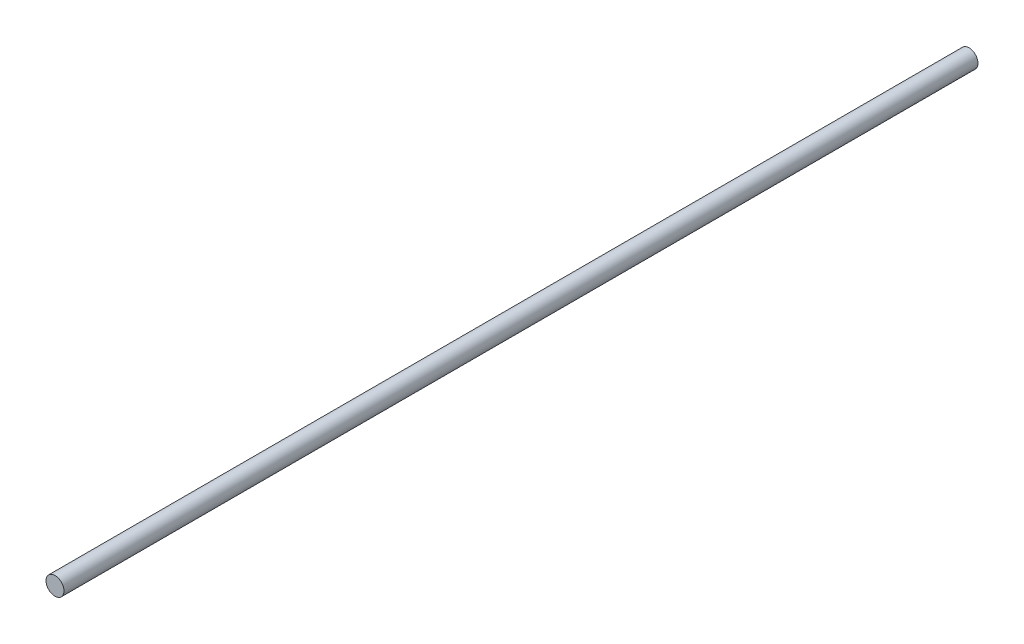
SolidWorks part; units mm, degrees
ref_plane "Front Plane" through (0, 0, 0) normal (0, 0, 1) x (1, 0, 0)
ref_plane "Top Plane" through (0, 0, 0) normal (0, 1, 0) x (1, 0, 0)
ref_plane "Right Plane" through (0, 0, 0) normal (1, 0, 0) x (0, 0, -1)
sketch "Sketch1" plane through (0, 0, 5) normal (0, 0, 1) x (1, 0, 0)
  circle A0 centre (1299.8728, 107.1307) radius 6 construction
  circle A1 centre (1299.8728, 107.1307) radius 6
extrude "Boss-Extrude1" add sketch "Sketch1" against normal up to surface (610 mm away)
